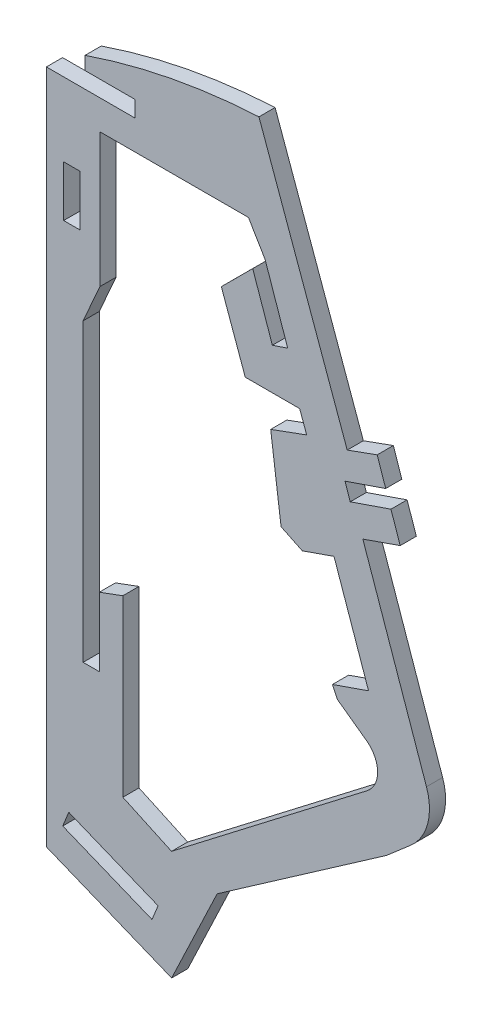
SolidWorks part; units mm, degrees
ref_plane "Front" through (0, 0, 0) normal (0, 0, 1) x (1, 0, 0)
ref_plane "Top" through (0, 0, 0) normal (0, 1, 0) x (1, 0, 0)
ref_plane "Right" through (0, 0, 0) normal (1, 0, 0) x (0, 0, -1)
sketch "Sketch1" plane through (0, 0, 0) normal (0, 0, 1) x (1, 0, 0)
  line L0 (1079.8769, -44.1052) -> (1068.0562, -10.173)
  line L1 (1068.0562, -10.173) -> (1074.9968, -7.7551)
  line L2 (1074.9968, -7.7551) -> (1073.2798, -2.7532)
  line L3 (1073.2798, -2.7532) -> (1065.7132, -5.3505)
  line L4 (1065.7132, -5.3505) -> (1064.7392, -2.513)
  line L5 (1064.7392, -2.513) -> (1072.3058, 0.0843)
  line L6 (1072.3058, 0.0843) -> (1070.7196, 4.7056)
  line L7 (1070.7196, 4.7056) -> (1065.1575, 2.6968)
  line L8 (1065.1575, 2.6968) -> (1048.7596, 48.1016)
  line L9 (1019.2139, 30.9259) -> (1019.2139, 6.0188)
  line L10 (1019.2139, 6.0188) -> (1016.1001, -1.0389)
  line L11 (1016.1001, -55.9767) -> (1016.1001, -1.0389)
  line L12 (1016.1001, -55.9767) -> (1019.1001, -55.9767)
  line L13 (1019.1001, -55.9767) -> (1019.1001, -43.1981)
  line L14 (1019.1001, -43.1981) -> (1023.4786, -41.5804)
  line L15 (1023.4786, -41.5804) -> (1023.4786, -73.9921)
  line L16 (1023.4786, -73.9921) -> (1032.5266, -78.167)
  line L17 (1032.5266, -78.167) -> (1068.8505, -50.2583)
  line L21 (1068.7348, -42.2424) -> (1063.3251, -38.329)
  line L22 (1063.3251, -38.329) -> (1062.4074, -36.386)
  line L23 (1062.4074, -36.386) -> (1069.1157, -34.0491)
  line L24 (1069.1157, -34.0491) -> (1062.7007, -15.6345)
  line L25 (1062.7007, -15.6345) -> (1056.8103, -17.6865)
  line L26 (1056.8103, -17.6865) -> (1052.8696, -15.7793)
  line L27 (1052.8696, -15.7793) -> (1050.9415, -1.0831)
  line L28 (1050.9415, -1.0831) -> (1057.6251, 1.3621)
  line L29 (1057.6251, 1.3621) -> (1056.321, 4.9484)
  line L30 (1056.321, 4.9484) -> (1046.2142, 4.9484)
  line L31 (1046.2142, 4.9484) -> (1041.7732, 17.2945)
  line L32 (1041.7732, 17.2945) -> (1047.6008, 23.112)
  line L33 (1047.6008, 23.112) -> (1051.2538, 12.6056)
  line L34 (1051.2538, 12.6056) -> (1054.1003, 13.5528)
  line L35 (1054.1003, 13.5528) -> (1049.9091, 25.7207)
  line L36 (1049.9091, 25.7207) -> (1046.8163, 30.9399)
  line L37 (1046.8163, 30.9399) -> (1019.2139, 30.9259)
  line L38 (1072.4404, -58.8762) -> (1040.9911, -80.7703)
  line L39 (1040.9911, -80.7703) -> (1032.5435, -98.5367)
  line L40 (1032.5435, -98.5367) -> (1009.2795, -89.074)
  line L41 (1009.2795, -89.074) -> (1009.2795, 36.3926)
  line L42 (1012.3078, -84.2073) -> (1013.4382, -81.4283)
  line L43 (1013.4382, -81.4283) -> (1030.0254, -88.1752)
  line L44 (1030.0254, -88.1752) -> (1028.895, -90.9542)
  line L45 (1028.895, -90.9542) -> (1012.3078, -84.2073)
  line L48 (1076.9711, -54.962) -> (1072.4404, -58.8762)
  line L49 (1035.7261, 39.3926) -> (1016.4663, 39.3926)
  line L50 (1035.7261, 36.3926) -> (1009.2795, 36.3926)
  line L56 (1015.483, 22.7319) -> (1015.483, 13.2819)
  line L57 (1015.483, 13.2819) -> (1012.483, 13.2819)
  line L58 (1012.483, 13.2819) -> (1012.483, 22.7319)
  line L59 (1012.483, 22.7319) -> (1015.483, 22.7319)
  line L60 (1016.4663, 41.8487) -> (1016.4663, 39.3926)
  line L61 (1035.7261, 39.3926) -> (1035.7261, 36.3926)
  arc A0 (1076.9711, -54.962) -> (1079.8769, -44.1052) centre (1070.4335, -47.3949) ccw
  arc A1 (1068.7348, -42.2424) -> (1068.8505, -50.2583) centre (1065.8042, -46.2935) cw
  arc A2 (1016.4663, 41.8487) -> (1048.7596, 48.1016) centre (1054.9098, -70.1773) cw
  dimension "D10" = 5
  dimension "D12" = 10
  dimension "D1" = 90
  dimension "D2" = 90
  dimension "D3" = 90
  dimension "D4" = 90
  dimension "D5" = 3
  dimension "D6" = 3
  dimension "D7" = 3
  dimension "D8" = 3
  dimension "D9" = 3
  dimension "D11" = 90
  dimension "D13" = 90
  dimension "D14" = 90
  dimension "D15" = 19.5
  dimension "D16" = 3
  dimension "D17" = 90
  dimension "D18" = 90
  dimension "D19" = 8
  dimension "D20" = 9.45
  dimension "D21" = 90
  dimension "D22" = 3
  dimension "D23" = 3
  dimension "D24" = 17.9068
extrude "Base-Extrude" add sketch "Sketch1" along normal blind 3
sketch "Sketch2" plane through (0, 0, 3) normal (0, 0, 1) x (1, 0, 0)
  line L0 (1035.7261, 36.3926) -> (1035.7261, 39.3926)
  line L1 (1035.7261, 39.3926) -> (1025.7261, 39.3926)
  line L2 (1025.7261, 39.3926) -> (1025.7261, 36.3926)
  line L3 (1035.7261, 36.3926) -> (1009.2795, 36.3926) construction
  line L4 (1025.7261, 36.3926) -> (1035.7261, 36.3926)
  dimension "D1" = 10
extrude "Boss-Extrude1" add sketch "Sketch2" against normal blind 3
